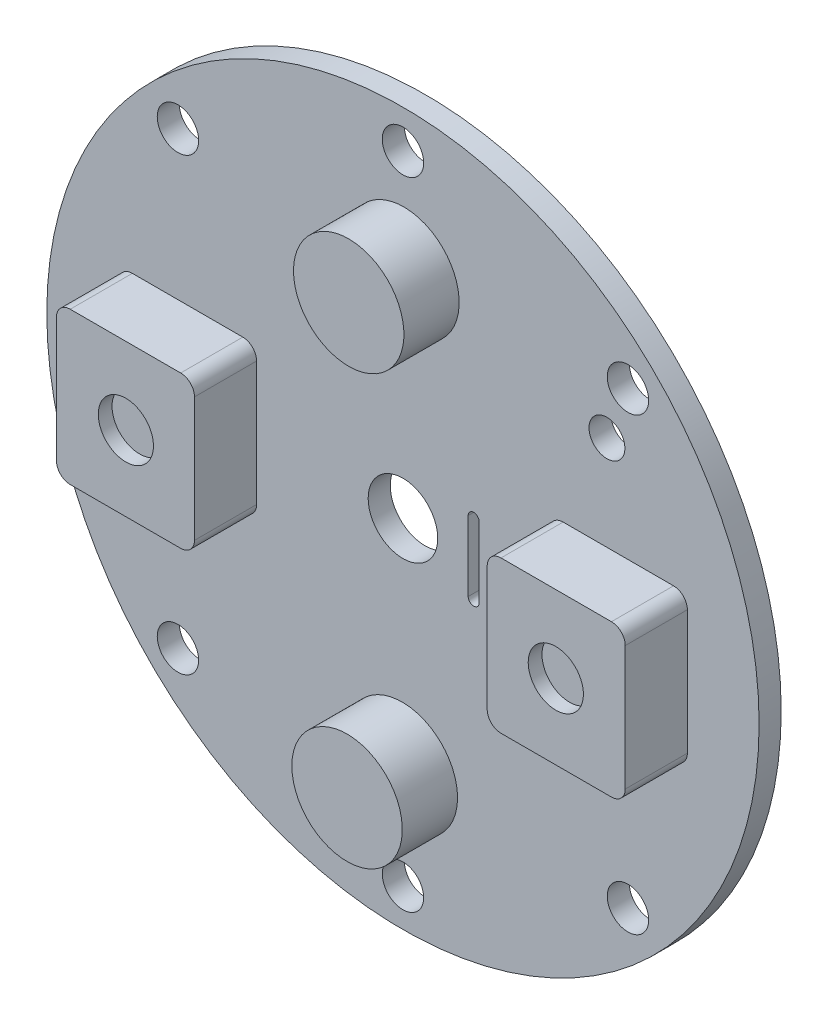
SolidWorks part; units mm, degrees
material "POM 乙缩醛共聚物"
ref_plane "前视基准面" through (0, 0, 0) normal (0, 0, 1) x (1, 0, 0)
ref_plane "上视基准面" through (0, 0, 0) normal (0, 1, 0) x (1, 0, 0)
ref_plane "右视基准面" through (0, 0, 0) normal (1, 0, 0) x (0, 0, -1)
sketch "草图1" plane through (0, 0, 0) normal (0, 0, 1) x (1, 0, 0)
  circle A0 centre (-24.6985, -1.5122) radius 25.8
  circle A1 centre (-24.6985, -1.5122) radius 2.52
  circle A2 centre (-24.6985, 21.5378) radius 1.5
  circle A3 centre (-40.9973, 14.7867) radius 1.5
  circle A5 centre (-40.9973, -17.811) radius 1.5
  circle A6 centre (-24.6985, -24.5622) radius 1.5
  circle A7 centre (-8.3997, -17.811) radius 1.5
  circle A9 centre (-8.3997, 14.7867) radius 1.5
  circle A10 centre (-47.7485, -1.5122) radius 1.5 [skipped]
  circle A11 centre (-1.6485, -1.5122) radius 1.5 [skipped]
  circle A13 centre (-9.9217, 10.9187) radius 1.3
  point P23 (-24.6985, -1.5122)
  dimension "D1" = 8
extrude "凸台-拉伸1" add sketch "草图1" against normal blind 1.6 from surface at -31.2004
sketch "草图3" plane through (0, 0, 0) normal (0, 0, 1) x (1, 0, 0)
  circle A0 centre (-24.6283, 14.0596) radius 4
  circle A1 centre (-24.7463, -17.0623) radius 4
extrude "凸台-拉伸2" add sketch "草图3" along normal blind 4 from surface at -31.2004 separate body starting at face at (-50.4985, -1.5122, -31.2004)
sketch "草图4" plane through (0, 0, 0) normal (0, 0, 1) x (1, 0, 0)
  line L3 (-4.0967, -1.4424) -> (-4.0967, 3.0576)
  line L4 (-4.0967, -1.4424) -> (-4.0967, -5.9424)
  line L5 (-5.0967, -6.9424) -> (-13.0967, -6.9424)
  line L6 (-5.0967, 4.0576) -> (-13.0967, 4.0576)
  line L7 (-14.0967, 3.0576) -> (-14.0967, -5.9424)
  line L8 (-35.3003, 3.0576) -> (-35.3003, -5.9424)
  line L9 (-44.3003, 4.0576) -> (-36.3003, 4.0576)
  line L10 (-44.3003, -6.9424) -> (-36.3003, -6.9424)
  line L11 (-45.3003, -1.4424) -> (-45.3003, -5.9424)
  line L12 (-45.3003, -1.4424) -> (-45.3003, 3.0576)
  arc A1 (-4.0967, -5.9424) -> (-5.0967, -6.9424) centre (-5.0967, -5.9424) cw
  arc A2 (-13.0967, -6.9424) -> (-14.0967, -5.9424) centre (-13.0967, -5.9424) cw
  arc A3 (-13.0967, 4.0576) -> (-14.0967, 3.0576) centre (-13.0967, 3.0576) ccw
  arc A4 (-4.0967, 3.0576) -> (-5.0967, 4.0576) centre (-5.0967, 3.0576) ccw
  arc A6 (-45.3003, 3.0576) -> (-44.3003, 4.0576) centre (-44.3003, 3.0576) cw
  arc A7 (-36.3003, 4.0576) -> (-35.3003, 3.0576) centre (-36.3003, 3.0576) cw
  arc A8 (-36.3003, -6.9424) -> (-35.3003, -5.9424) centre (-36.3003, -5.9424) ccw
  arc A9 (-45.3003, -5.9424) -> (-44.3003, -6.9424) centre (-44.3003, -5.9424) ccw
  dimension "D1" = 1
extrude "凸台-拉伸3" add sketch "草图4" along normal blind 4.5 from surface at -31.2004 separate body starting at face at (-50.4985, -1.5122, -31.2004)
sketch "草图5" plane through (0, 0, 0) normal (0, 0, 1) x (1, 0, 0)
  circle A1 centre (-9.1266, -1.5122) radius 2
  circle A2 centre (-40.2704, -1.5122) radius 2
extrude "切除-拉伸1" cut sketch "草图5" against normal blind 1 from surface at -26.7004 starting at face at (-40.3003, -1.4424, -26.7004)
sketch "草图6" plane through (0, 0, 0) normal (0, 0, 1) x (1, 0, 0)
  line L6 (-19.1746, 1.0278) -> (-19.1746, -4.0522)
  line L7 (-19.9746, 1.0278) -> (-19.9746, -4.0522)
  arc A0 (-19.1746, -4.0522) -> (-19.9746, -4.0522) centre (-19.5746, -4.0522) cw
  arc A1 (-19.1746, 1.0278) -> (-19.9746, 1.0278) centre (-19.5746, 1.0278) ccw
extrude "切除-拉伸2" cut sketch "草图6" along normal up to surface (1.6 mm away) from surface at -32.8004 up to face at (-50.4985, -1.5122, -31.2004) starting at face at (-9.8997, -17.811, -32.8004)
